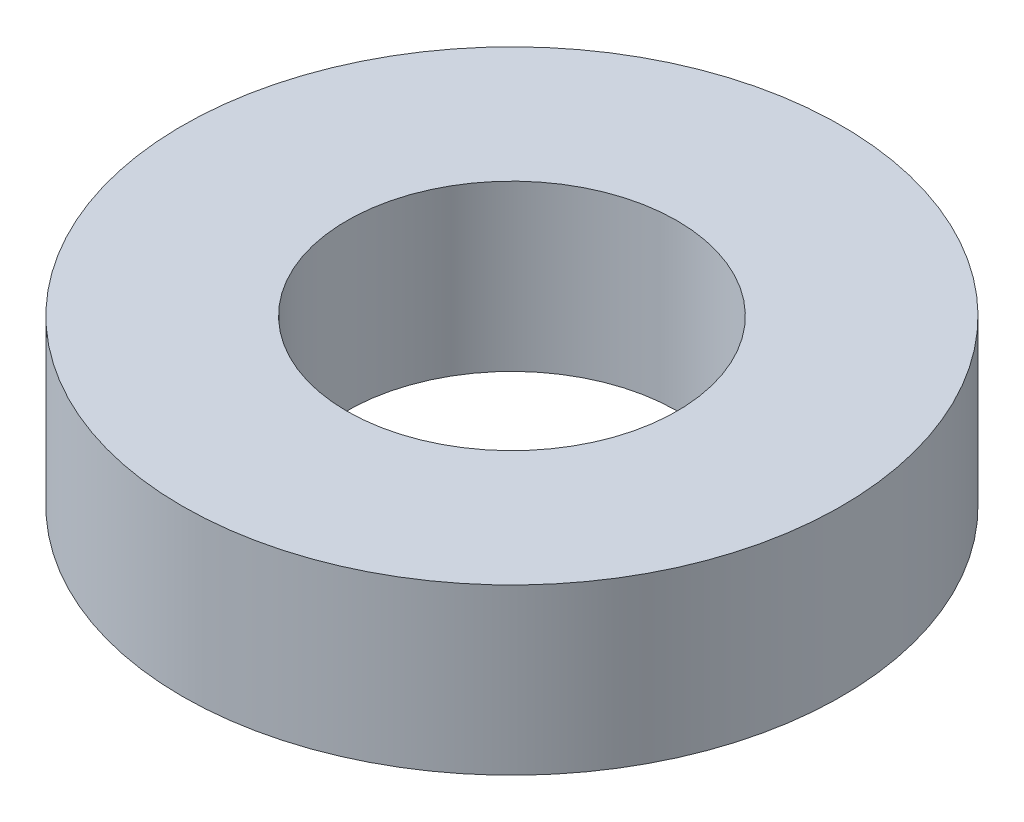
SolidWorks part; units mm, degrees
material "Plain Carbon Steel"
ref_plane "Front Plane" through (0, 0, 0) normal (0, 0, 1) x (1, 0, 0)
ref_plane "Top Plane" through (0, 0, 0) normal (0, 1, 0) x (1, 0, 0)
ref_plane "Right Plane" through (0, 0, 0) normal (1, 0, 0) x (0, 0, -1)
sketch "Sketch1" plane through (0, 0, 0) normal (0, 1, 0) x (1, 0, 0)
  circle A0 centre (0, 0) radius 25.4
  circle A1 centre (0, 0) radius 12.721
  dimension "D1" = 50.8
  dimension "D2" = 25.4419
extrude "Boss-Extrude1" add sketch "Sketch1" along normal blind 12.7
